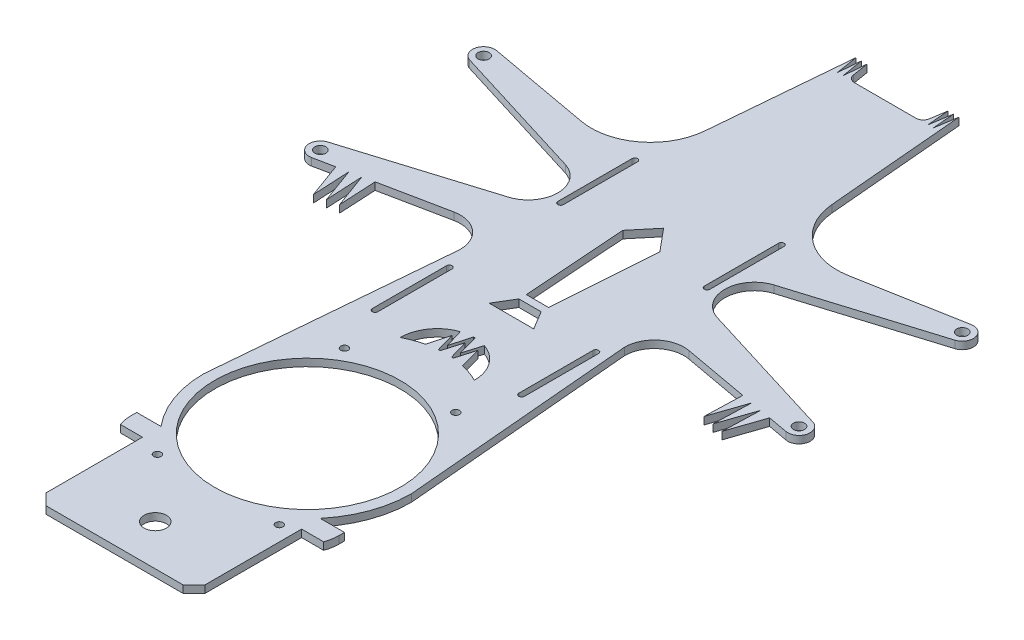
SolidWorks part; units mm, degrees
ref_plane "前视基准面" through (0, 0, 0) normal (0, 0, 1) x (1, 0, 0)
ref_plane "上视基准面" through (0, 0, 0) normal (0, 1, 0) x (1, 0, 0)
ref_plane "右视基准面" through (0, 0, 0) normal (1, 0, 0) x (0, 0, -1)
sketch "草图1" plane through (0, 0, 0) normal (0, 1, 0) x (1, 0, 0)
  line L5 (-65.3843, -19.1333) -> (-28.1418, -7.6445)
  line L6 (-63.9021, -24.9398) -> (-58.5124, -23.8437)
  line L8 (0, 0) -> (0, 91.5573) construction
  line L9 (0, 0) -> (-115.8836, 0) construction
  line L15 (0, 0) -> (0, -124.2991) construction
  line L16 (-15, -65) -> (15, -65) construction
  line L20 (-15.42, -115) -> (17.43, -115) construction
  line L21 (-28, -109.5) -> (-28, -90)
  line L22 (28, -109.5) -> (28, -90)
  line L23 (-17.5, -120) -> (17.5, -120)
  line L28 (22.5, -27) -> (22.5, 27) construction
  line L29 (-22.5, -27) -> (-22.5, 27) construction
  line L30 (28.1418, -7.6445) -> (65.3843, -19.1333)
  line L31 (28.1418, 7.6445) -> (65.3843, 19.1333)
  line L32 (-28, -90) -> (28, -90) construction
  line L33 (28, -90) -> (22.5, -27)
  line L34 (-28, -90) -> (-22.5, -27)
  line L35 (63.9635, -24.9516) -> (58.5521, -23.968)
  line L36 (0, 0) -> (104.501, 0) construction
  line L37 (-28.1418, 7.6445) -> (-65.3843, 19.1333)
  line L39 (22.5, 70) -> (22.5, 27) construction
  line L40 (-22.5, 70) -> (-22.5, 27) construction
  line L41 (31.9307, 19.129) -> (63.9635, 24.9516) construction
  line L42 (-63.9635, 24.9516) -> (-31.9307, 19.129) construction
  line L43 (-17.1562, 34.2114) -> (-13.885, 71.6811)
  line L44 (63.9635, 24.9516) -> (35.957, 19.8608)
  line L45 (-63.9635, 24.9516) -> (-35.957, 19.8608)
  line L46 (17.1562, 34.2114) -> (13.885, 71.6811)
  line L47 (51.4721, -37.7563) -> (54.614, -20.4713) construction
  line L48 (43.8626, -31.4617) -> (59.0167, -34.2163) construction
  line L49 (52.3363, -33.002) -> (52.6489, -22.895)
  line L50 (52.3363, -33.002) -> (55.6005, -23.4315)
  line L51 (-51.727, -34.6283) -> (-54.8464, -19.2902) construction
  line L52 (-52.1098, -32.7462) -> (-52.6328, -22.6479)
  line L53 (-52.1098, -32.7462) -> (-55.5726, -23.2458)
  line L54 (-55.5726, -23.2458) -> (-55.0496, -33.3441)
  line L55 (-55.0496, -33.3441) -> (-58.5124, -23.8437)
  line L56 (-52.6328, -22.6479) -> (-49.1699, -32.1484)
  line L57 (-49.1699, -32.1484) -> (-49.693, -22.05)
  line L58 (-56.8438, -33.709) -> (-45.8391, -31.4709) construction
  line L59 (-49.693, -22.05) -> (-32.0641, -18.4647)
  line L60 (49.3846, -32.4655) -> (49.6972, -22.3584)
  line L61 (49.3846, -32.4655) -> (52.6489, -22.895)
  line L62 (55.2879, -33.5385) -> (55.6005, -23.4315)
  line L63 (55.2879, -33.5385) -> (58.5521, -23.968)
  line L64 (49.6972, -22.3584) -> (31.9307, -19.129)
  line L65 (-14.4088, 65.6811) -> (14.4088, 65.6811) construction
  line L66 (-13.885, 71.6811) -> (-12.9088, 65.6811)
  line L67 (-12.9088, 65.6811) -> (-12.385, 71.6811)
  line L68 (-12.385, 71.6811) -> (-11.4088, 65.6811)
  line L69 (-11.4088, 65.6811) -> (-10.885, 71.6811)
  line L70 (-10.885, 71.6811) -> (-10.1819, 67.3599)
  line L71 (13.885, 71.6811) -> (12.9484, 65.6811)
  line L72 (12.9484, 65.6811) -> (12.4246, 71.6811)
  line L73 (12.4246, 71.6811) -> (11.4881, 65.6811)
  line L74 (11.4881, 65.6811) -> (10.9643, 71.6811)
  line L75 (10.9643, 71.6811) -> (10.2918, 67.3727)
  line L76 (-8.2079, 65.6811) -> (8.3157, 65.6811)
  circle A0 centre (-64.5, 30) radius 1.5 construction
  circle A1 centre (64.5, 30) radius 1.5 construction
  circle A2 centre (64.5, -30) radius 1.5 construction
  circle A3 centre (-64.5, -30) radius 1.5 construction
  circle A4 centre (-64.5, 30) radius 3 construction
  circle A5 centre (64.5, 30) radius 3 construction
  circle A6 centre (64.5, -30) radius 3 construction
  circle A7 centre (-64.5, -30) radius 3 construction
  circle A10 centre (-64.5, 22) radius 1.5
  circle A11 centre (64.5, 22) radius 1.5
  circle A12 centre (64.5, -22) radius 1.5
  circle A13 centre (-64.5, -22) radius 1.5
  circle A22 centre (0, -90) radius 25
  circle A23 centre (-15, -65) radius 1
  circle A24 centre (15, -65) radius 1
  circle A25 centre (-15.42, -115) radius 1
  circle A26 centre (17.43, -115) radius 1
  arc A27 (-17.5, -120) -> (-28, -109.5) centre (-17.5, -109.5) cw
  arc A28 (17.5, -120) -> (28, -109.5) centre (17.5, -109.5) ccw
  arc A42 (63.9635, -24.9516) -> (65.3843, -19.1333) centre (64.5, -22) ccw
  arc A43 (65.3843, 19.1333) -> (63.9635, 24.9516) centre (64.5, 22) ccw
  arc A44 (28.1418, -7.6445) -> (28.1418, 7.6445) centre (30.5, 0) cw
  arc A46 (22.5, -27) -> (31.9307, -19.129) centre (30.5, -27) cw
  arc A47 (-65.3843, -19.1333) -> (-63.9021, -24.9398) centre (-64.5, -22) ccw
  arc A49 (-28.1418, -7.6445) -> (-28.1418, 7.6445) centre (-30.5, 0) ccw
  arc A50 (-22.5, -27) -> (-32.0641, -18.4647) centre (-30.4697, -26.3042) ccw
  arc A51 (-63.9635, 24.9516) -> (-65.3843, 19.1333) centre (-64.5, 22) ccw
  arc A52 (31.9307, 19.129) -> (22.5, 27) centre (30.5, 27) cw construction
  arc A53 (-31.9307, 19.129) -> (-22.5, 27) centre (-30.5, 27) ccw construction
  arc A54 (-35.957, 19.8608) -> (-17.1562, 34.2114) centre (-33.0955, 35.6029) ccw
  arc A55 (17.1562, 34.2114) -> (35.957, 19.8608) centre (33.0955, 35.6029) ccw
  arc A56 (-8.2079, 65.6811) -> (-10.1819, 67.3599) centre (-8.2079, 67.6811) cw
  arc A57 (10.2918, 67.3727) -> (8.3157, 65.6811) centre (8.3157, 67.6811) cw
  point P0 (0, 0)
  point P109 (-9.9088, 65.6811)
  point P112 (10.0277, 65.6811)
  dimension "D1" = 3
  dimension "D6" = 6
  dimension "D7" = 6
  dimension "D8" = 6
  dimension "D9" = 6
  dimension "D15" = 3
  dimension "D18" = 6
  dimension "D19" = 16
  dimension "D20" = 8
  dimension "D21" = 22
  dimension "D22" = 50
  dimension "D28" = 2
  dimension "D31" = 2
  dimension "D25" = 45
  dimension "D37" = 27
  dimension "D38" = 16
  dimension "D39" = 10
  dimension "D40" = 6
  dimension "D41" = 6
  dimension "D44" = 8
  dimension "D45" = 8
  dimension "D27" = 22.5
  dimension "D47" = 10.5
  dimension "D48" = 10
  dimension "D17" = 8
  dimension "D12" = 6
  dimension "D13" = 8
  dimension "D16" = 8
  dimension "D60" = 2
  dimension "D61" = 2
  dimension "D2" = 129
  dimension "D3" = 60
  dimension "D4" = 30
  dimension "D5" = 64.5
  dimension "D10" = 27
  dimension "D11" = 27
  dimension "D14" = 19.9365
  dimension "D23" = 30
  dimension "D24" = 15
  dimension "D26" = 30
  dimension "D29" = 32.85
  dimension "D30" = 2.43
  dimension "D32" = 27
  dimension "D33" = 28
  dimension "D34" = 28
  dimension "D35" = 35
  dimension "D36" = 17.5
  dimension "D42" = 45
  dimension "D43" = 22.5
  dimension "D46" = 120
  dimension "D49" = 10
  dimension "D50" = 3
  dimension "D51" = 3
  dimension "D52" = 3
  dimension "D53" = 1.5
  dimension "D54" = 10
  dimension "D55" = 3
  dimension "D56" = 1.5
  dimension "D57" = 65.6811
  dimension "D58" = 6
  dimension "D59" = 1.5
extrude "凸台-拉伸1" add sketch "草图1" along normal blind 2
sketch "草图2" plane through (0, 0, 0) normal (0, -1, 0) x (1, 0, 0)
  line L0 (0, 133.3282) -> (0, -97.043) construction
  line L1 (-19.75, 2) -> (-19.75, -18) construction
  line L2 (-19, 2) -> (-19, -18)
  line L3 (-20.5, 2) -> (-20.5, -18)
  line L4 (19.75, 2) -> (19.75, -18) construction
  line L5 (20.5, 2) -> (20.5, -18)
  line L6 (19, 2) -> (19, -18)
  line L7 (0, 0) -> (56.7659, 0) construction
  line L8 (-19.75, 52) -> (-19.75, 32) construction
  line L9 (-19, 52) -> (-19, 32)
  line L10 (-20.5, 52) -> (-20.5, 32)
  line L11 (19.75, 52) -> (19.75, 32) construction
  line L12 (20.5, 52) -> (20.5, 32)
  line L13 (19, 52) -> (19, 32)
  arc A0 (-19, 2) -> (-20.5, 2) centre (-19.75, 2) ccw
  arc A1 (-20.5, -18) -> (-19, -18) centre (-19.75, -18) ccw
  arc A2 (20.5, 2) -> (19, 2) centre (19.75, 2) ccw
  arc A3 (19, -18) -> (20.5, -18) centre (19.75, -18) ccw
  arc A4 (-19, 52) -> (-20.5, 52) centre (-19.75, 52) ccw
  arc A5 (-20.5, 32) -> (-19, 32) centre (-19.75, 32) ccw
  arc A6 (20.5, 52) -> (19, 52) centre (19.75, 52) ccw
  arc A7 (19, 32) -> (20.5, 32) centre (19.75, 32) ccw
  arc A8 (-10, 55) -> (10, 55) centre (0, 55) ccw
  arc A9 (-10, 55) -> (10, 55) centre (0, 74.5959) ccw
  point P5 (-19.75, -8)
  point P10 (19.75, -8)
  point P19 (-19.75, 42)
  point P26 (19.75, 42)
  dimension "D6" = 42
  dimension "D8" = 10
  dimension "D9" = 22
  dimension "D1" = 1.5
  dimension "D2" = 20
  dimension "D3" = 19
  dimension "D4" = 19
  dimension "D5" = 8
  dimension "D7" = 55
  dimension "D10" = 10
extrude "切除-拉伸1" cut sketch "草图2" against normal blind 10
sketch "草图3" plane through (0, 0, 0) normal (0, -1, 0) x (1, 0, 0)
  line L0 (0, 67.5428) -> (0, 43.0807) construction
  line L1 (-3.5, 60.2388) -> (-3.5, 43.3854) construction
  line L2 (3.5, 60.0167) -> (3.5, 43.3854) construction
  line L3 (-1.5, 52.6471) -> (0, 47.5)
  line L4 (0, 47.5) -> (1.5, 52.6471)
  line L5 (-5.2946, 47.5) -> (4.5072, 47.5) construction
  line L6 (-3.5, 47.5) -> (-2, 52.687)
  line L7 (-5, 53.1716) -> (-3.5, 47.5)
  line L8 (3.5, 47.5) -> (2, 52.687)
  line L9 (3.5, 47.5) -> (5, 53.1716)
  line L10 (-5.8174, 50.5) -> (6.3675, 50.5) construction
  line L11 (-5.8021, 45) -> (6.2608, 45) construction
  line L12 (-1.75, 52.0659) -> (-1.75, 44.2103) construction
  line L13 (1.75, 52.0659) -> (1.75, 43.5429) construction
  line L14 (-1.75, 50.5) -> (-0.25, 45.0031)
  line L15 (-1.75, 50.5) -> (-3.25, 45.5429)
  line L16 (1.75, 50.5) -> (0.25, 45.0031)
  line L17 (1.75, 50.5) -> (3.25, 45.5429)
  line L18 (-5, 53.1716) -> (-5, 54.1716)
  line L19 (-5, 54.1716) -> (5, 54.1716)
  line L20 (5, 54.1716) -> (5, 53.1716)
  line L21 (-2, 52.687) -> (-2, 53.687)
  line L22 (-2, 53.687) -> (-1.5, 53.687)
  line L23 (-1.5, 53.687) -> (-1.5, 52.6471)
  line L24 (1.5, 52.6471) -> (1.5, 53.687)
  line L25 (1.5, 53.687) -> (2, 53.687)
  line L26 (2, 53.687) -> (2, 52.687)
  line L27 (-3.25, 45.5429) -> (-3.25, 43.5429)
  line L28 (-3.25, 43.5429) -> (3.25, 43.5429)
  line L29 (3.25, 43.5429) -> (3.25, 45.5429)
  line L30 (-0.25, 45.0031) -> (-0.25, 44.0031)
  line L31 (-0.25, 44.0031) -> (0.25, 44.0031)
  line L32 (0.25, 44.0031) -> (0.25, 45.0031)
  arc A0 (-10, 55) -> (10, 55) centre (0, 74.5959) ccw construction
  arc A1 (-10, 55) -> (10, 55) centre (0, 74.5959) ccw construction
  arc A2 (-10, 55) -> (10, 55) centre (0, 55) ccw construction
  arc A3 (-10, 55) -> (10, 55) centre (0, 55) ccw construction
  dimension "D1" = 3.5
  dimension "D2" = 3.5
  dimension "D3" = 7.5
  dimension "D4" = 3
  dimension "D5" = 1.5
  dimension "D6" = 1.5
  dimension "D7" = 1.5
  dimension "D8" = 3
  dimension "D9" = 1.5
  dimension "D10" = 5.5
  dimension "D11" = 1.75
  dimension "D12" = 3.5
  dimension "D13" = 1.5
  dimension "D14" = 1.5
  dimension "D15" = 1.5
  dimension "D16" = 1.5
  dimension "D17" = 1
  dimension "D18" = 1
  dimension "D19" = 1
  dimension "D20" = 2
extrude "凸台-拉伸2" add sketch "草图3" against normal blind 2
sketch "草图4" plane through (0, 0, 0) normal (0, -1, 0) x (1, 0, 0)
  line L0 (0, 0) -> (0, 140.5969) construction
  line L1 (-28, 108) -> (-21.4476, 108)
  line L2 (-17.5, 120) -> (17.5, 120) construction
  line L3 (-28, 90) -> (28, 90) construction
  line L4 (-28, 90) -> (-28, 109.5) construction
  line L5 (28, 109.5) -> (28, 90) construction
  line L6 (-21.4476, 113) -> (-21.4476, 119.2297)
  line L7 (21.4476, 119.2297) -> (21.4476, 113)
  line L8 (21.4476, 108) -> (28, 108)
  line L9 (-21.4476, 113) -> (-27.3995, 113)
  line L10 (21.4476, 113) -> (27.3995, 113)
  line L11 (-28, 108) -> (-28, 90)
  line L12 (28, 108) -> (28, 90)
  circle A0 centre (0, 90) radius 25 construction
  circle A1 centre (0, 90) radius 25 construction
  arc A2 (-21.4476, 108) -> (-28, 90) centre (0, 90) ccw
  arc A3 (28, 90) -> (21.4476, 108) centre (0, 90) ccw
  arc A4 (-17.5, 120) -> (-28, 109.5) centre (-17.5, 109.5) ccw construction
  arc A5 (28, 109.5) -> (17.5, 120) centre (17.5, 109.5) ccw construction
  arc A6 (-21.4476, 119.2297) -> (-27.3995, 113) centre (-17.5, 109.5) ccw
  arc A7 (27.3995, 113) -> (21.4476, 119.2297) centre (17.5, 109.5) ccw
  dimension "D1" = 12
  dimension "D4" = 5
  dimension "D5" = 5
extrude "切除-拉伸2" cut sketch "草图4" against normal blind 2
sketch "草图5" plane through (0, 0, 0) normal (0, -1, 0) x (1, 0, 0)
  line L0 (-6, 35) -> (6, 35)
  line L1 (6, 35) -> (3, 30)
  line L2 (3, 30) -> (-3, 30)
  line L3 (-3, 30) -> (-6, 35)
  line L4 (-3, 28) -> (3, 28)
  line L5 (3, 28) -> (5, 0)
  line L6 (5, 0) -> (0, -6)
  line L7 (0, -6) -> (-5, 0)
  line L8 (-5, 0) -> (-3, 28)
  dimension "D1" = 12
  dimension "D2" = 6
  dimension "D3" = 3
  dimension "D4" = 30
  dimension "D5" = 5
  dimension "D6" = 2
  dimension "D7" = 6
  dimension "D8" = 10
extrude "切除-拉伸3" cut sketch "草图5" against normal blind 2
sketch "草图6" plane through (0, 0, 0) normal (0, -1, 0) x (1, 0, 0)
  line L0 (-21.4476, 119.2297) -> (-21.4476, 139)
  line L1 (-18.4476, 142) -> (18.4476, 142)
  line L2 (21.4476, 139) -> (21.4476, 119.2297)
  line L3 (-17.5, 120) -> (17.5, 120) construction
  line L4 (0, 0) -> (0, 166.5632) construction
  line L5 (-21.4476, 131) -> (21.4476, 131) construction
  line L6 (-21.4476, 139) -> (-18.4476, 142)
  line L7 (18.4476, 142) -> (21.4476, 139)
  line L8 (-21.4476, 119.2297) -> (21.4476, 119.2297)
  circle A0 centre (0, 131) radius 3
  point P1 (-21.4476, 142)
  point P4 (21.4476, 142)
  dimension "D3" = 6
  dimension "D1" = 22
  dimension "D2" = 11
extrude "凸台-拉伸3" add sketch "草图6" against normal blind 2
